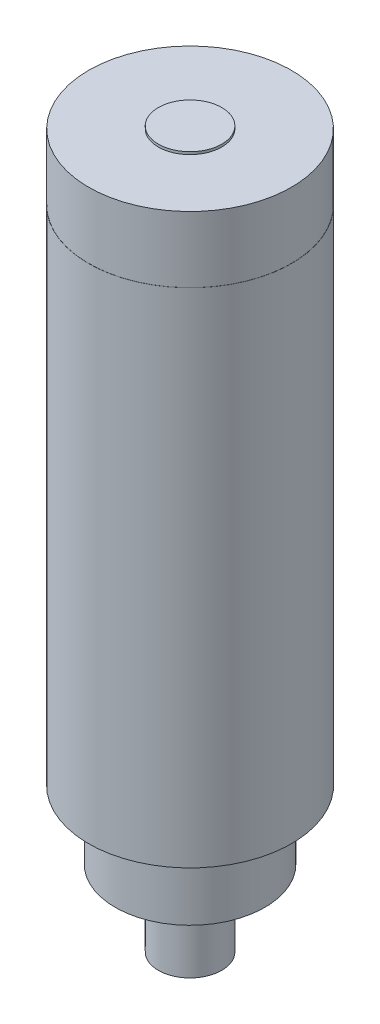
SolidWorks part; units mm, degrees
ref_plane "Plan de face" through (0, 0, 0) normal (0, 0, 1) x (1, 0, 0)
ref_plane "Plan de dessus" through (0, 0, 0) normal (0, 1, 0) x (1, 0, 0)
ref_plane "Plan de droite" through (0, 0, 0) normal (1, 0, 0) x (0, 0, -1)
sketch "Esquisse2" plane through (0, 0, 0) normal (0, 0, 1) x (1, 0, 0)
  line L0 (0, 0) -> (12.5, 0)
  line L1 (12.5, 0) -> (12.5, 30)
  line L2 (12.5, 30) -> (29.5, 30)
  line L3 (29.5, 30) -> (29.5, 57)
  line L4 (29.5, 57) -> (40, 57)
  line L5 (40, 57) -> (40, 255)
  line L6 (40, 255) -> (39.95, 255)
  line L7 (39.95, 255) -> (39.95, 281)
  line L8 (39.95, 281) -> (12.5, 281)
  line L9 (12.5, 281) -> (12.5, 282)
  line L10 (12.5, 282) -> (0, 282)
  line L11 (0, 282) -> (0, 0) construction
  line L12 (0, 0) -> (0, 282)
  dimension "D1" = 26
  dimension "D2" = 30
  dimension "D3" = 27
  dimension "D4" = 198
  dimension "D5" = 1
  dimension "D6" = 80
  dimension "D7" = 79.9
  dimension "D8" = 59
  dimension "D9" = 25
  dimension "D10" = 25
revolve "Révolution1" add sketch "Esquisse2" angle 360 about L11
